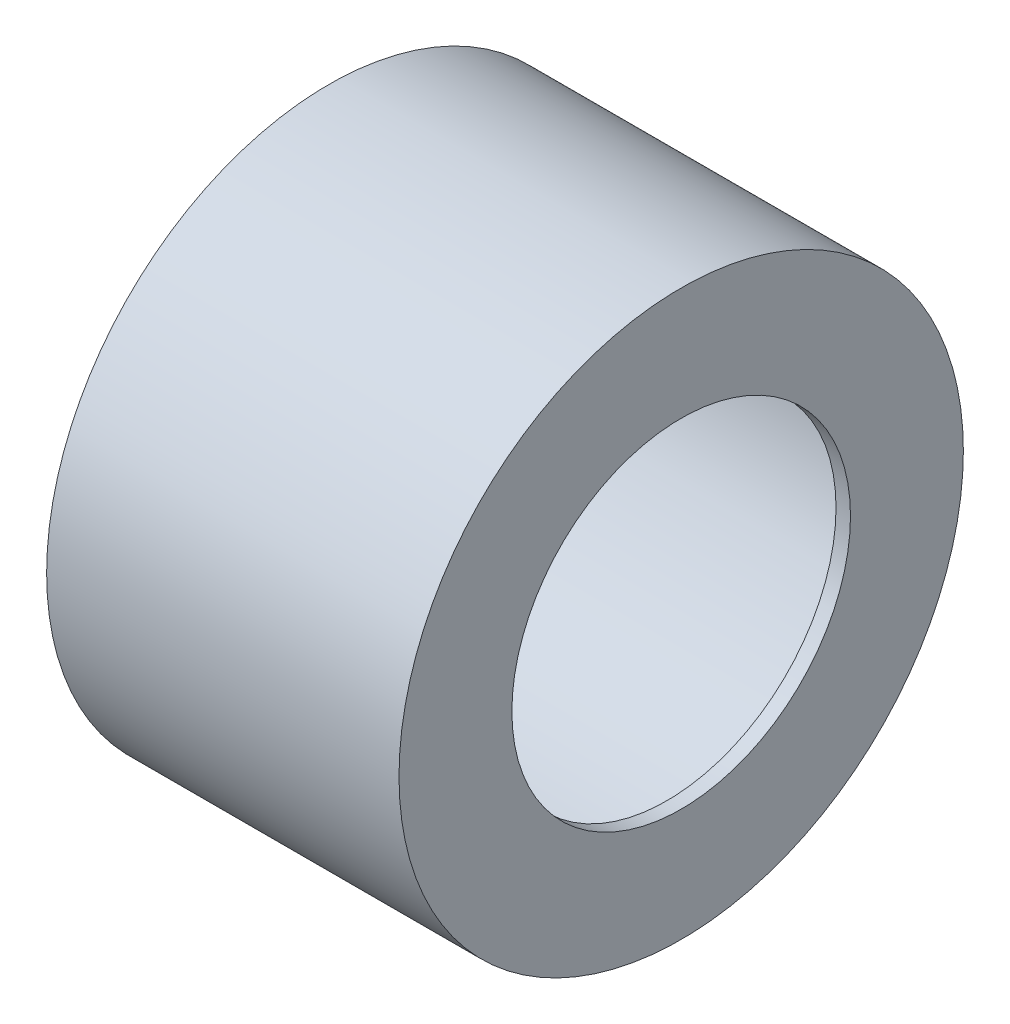
SolidWorks part; units mm, degrees
ref_plane "Front Plane" through (0, 0, 0) normal (0, 0, 1) x (1, 0, 0)
ref_plane "Top Plane" through (0, 0, 0) normal (0, 1, 0) x (1, 0, 0)
ref_plane "Right Plane" through (0, 0, 0) normal (1, 0, 0) x (0, 0, -1)
sketch "Axial profile (mm)" plane through (0, 0, 0) normal (0, 0, 1) x (1, 0, 0)
  line L0 (-110, 0) -> (75, 0) construction
  line L1 (135.7, 36.4) -> (182.4, 36.4)
  line L2 (182.4, 36.4) -> (182.4, 23.4)
  line L3 (182.4, 23.4) -> (184.4, 23.4)
  line L4 (184.4, 23.4) -> (184.4, 39)
  line L5 (184.4, 39) -> (135.7, 39)
  line L6 (135.7, 39) -> (135.7, 36.4)
revolve "Full revolution" add sketch "Axial profile (mm)" angle 360 about L0
